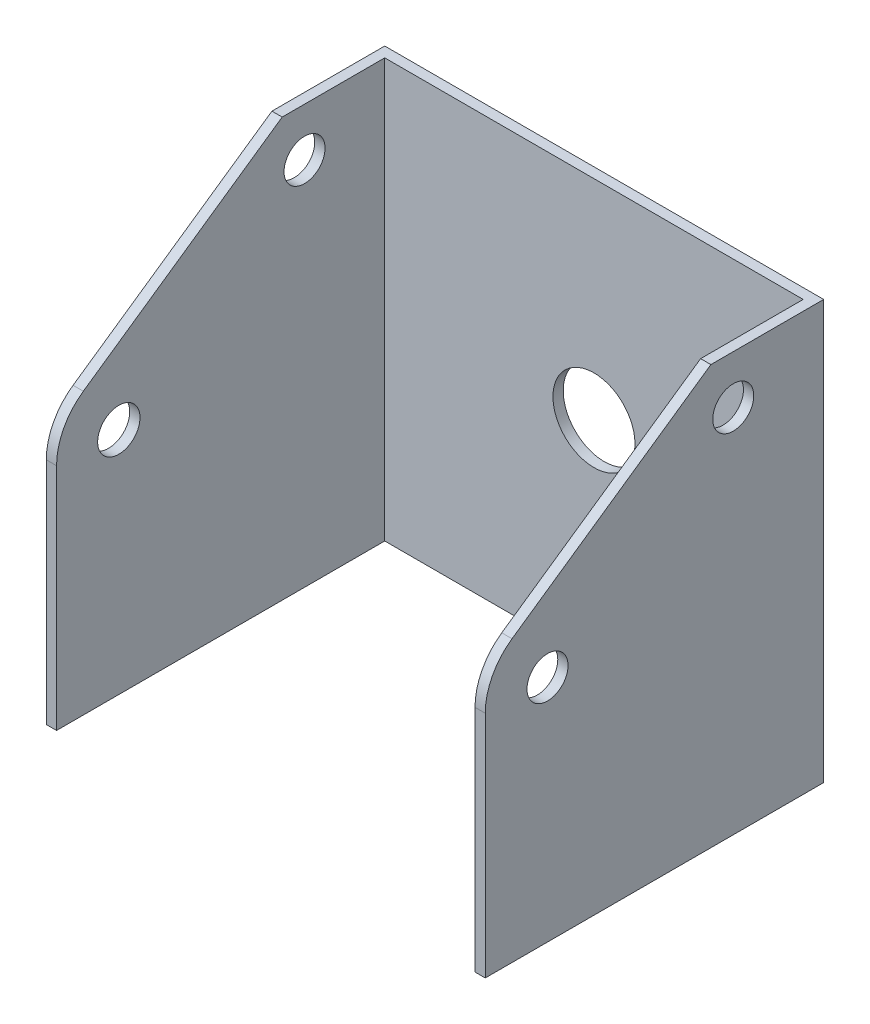
SolidWorks part; units mm, degrees
material "6061 Alloy"
ref_plane "Front Plane" through (0, 0, 0) normal (0, 0, 1) x (1, 0, 0)
ref_plane "Top Plane" through (0, 0, 0) normal (0, 1, 0) x (1, 0, 0)
ref_plane "Right Plane" through (0, 0, 0) normal (1, 0, 0) x (0, 0, -1)
sketch "Sketch1" plane through (0, 0, 0) normal (0, 0, 1) x (1, 0, 0)
  line L1 (-102, -102) -> (102, -102)
  line L2 (-102, -102) -> (-102, 102)
  line L3 (-102, 102) -> (102, 102)
  line L4 (102, -102) -> (102, 102)
  circle A0 centre (0, 0) radius 20
  point P0 (0, 0)
extrude "Boss-Extrude1" add sketch "Sketch1" along normal blind 5
sketch "Sketch2" plane through (102, 0, 0) normal (1, 0, 0) x (0, 0, -1)
  line L0 (0, 102) -> (-55, 102)
  line L1 (0, -102) -> (0, 102)
  line L2 (-165, -102) -> (-165, 9.7843)
  line L3 (0, -102) -> (-55, -102)
  line L4 (-165, -102) -> (-55, -102)
  line L5 (-55, 102) -> (-151.9507, 34.723)
  arc A1 (-151.9507, 34.723) -> (-165, 9.7843) centre (-134.645, 9.7843) ccw
  circle A2 centre (-44.1072, 78.451) radius 10
  circle A5 centre (-134.645, 9.7843) radius 10
extrude "Boss-Extrude2" add sketch "Sketch2" along normal blind 5
sketch "Sketch3" plane through (-102, 0, 0) normal (-1, 0, 0) x (0, 0, 1)
  line L0 (0, 102) -> (0, -102)
  line L1 (0, -102) -> (165, -102)
  line L2 (165, 9.7843) -> (165, -102)
  line L3 (0, 102) -> (55, 102)
  line L4 (55, 102) -> (151.9507, 34.723)
  arc A0 (165, 9.7843) -> (151.9507, 34.723) centre (134.645, 9.7843) ccw
  circle A2 centre (44.1072, 78.451) radius 10
  circle A3 centre (134.645, 9.7843) radius 10.3257
extrude "Boss-Extrude3" add sketch "Sketch3" along normal blind 5
